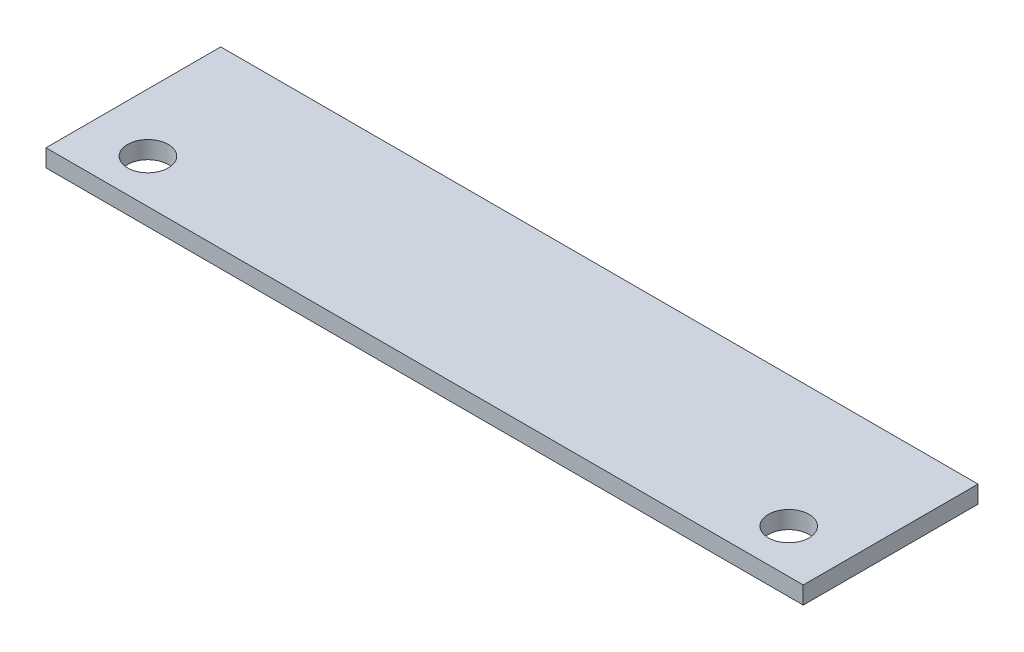
SolidWorks part; units mm, degrees
material "ASTM A36 Steel"
ref_plane "Front Plane" through (0, 0, 0) normal (0, 0, 1) x (1, 0, 0)
ref_plane "Top Plane" through (0, 0, 0) normal (0, 1, 0) x (1, 0, 0)
ref_plane "Right Plane" through (0, 0, 0) normal (1, 0, 0) x (0, 0, -1)
sketch "Sketch1" plane through (0, 0, 0) normal (0, 1, 0) x (1, 0, 0)
  line L1 (-130, -30) -> (130, -30)
  line L2 (-130, -30) -> (-130, 30)
  line L3 (-130, 30) -> (130, 30)
  line L4 (130, -30) -> (130, 30)
  line L5 (-130, -30) -> (130, 30) construction
  line L6 (-130, 30) -> (130, -30) construction
  point P0 (0, 0)
  dimension "D1" = 260
  dimension "D2" = 60
extrude "Boss-Extrude1" add sketch "Sketch1" along normal blind 6
sketch "Sketch2" plane through (0, 6, 0) normal (0, 1, 0) x (1, 0, 0)
  line L0 (-130, -30) -> (130, -30) construction
  line L1 (130, -30) -> (130, 30) construction
  line L2 (-130, 30) -> (-130, -30) construction
  circle A0 centre (110, -15) radius 7
  circle A1 centre (-110, -15) radius 7
  dimension "D1" = 14
  dimension "D2" = 15
  dimension "D3" = 20
  dimension "D4" = 14
  dimension "D5" = 20
  dimension "D6" = 15
extrude "Cut-Extrude1" cut sketch "Sketch2" against normal through all both and the other way through all
